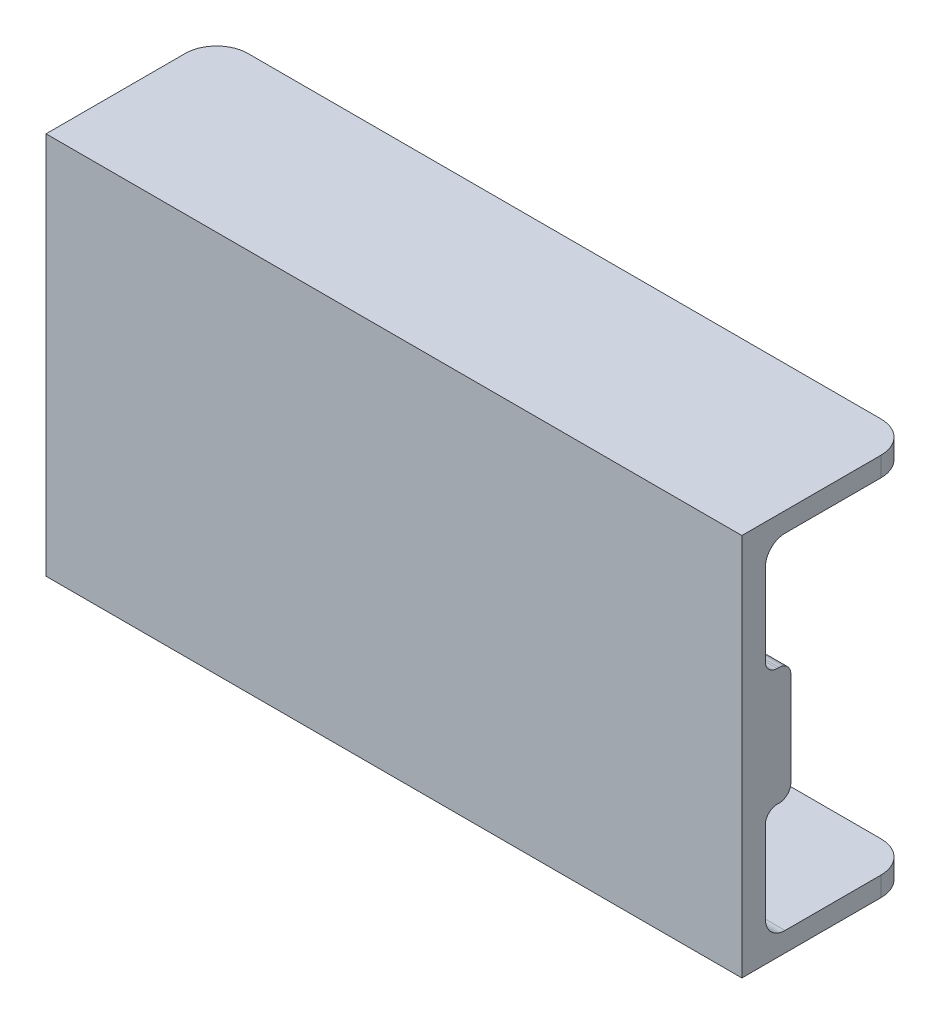
SolidWorks part; units mm, degrees
ref_plane "Front Plane" through (0, 0, 0) normal (0, 0, 1) x (1, 0, 0)
ref_plane "Top Plane" through (0, 0, 0) normal (0, 1, 0) x (1, 0, 0)
ref_plane "Right Plane" through (0, 0, 0) normal (1, 0, 0) x (0, 0, -1)
sketch "Sketch1" plane through (0, 0, 0) normal (0, 0, 1) x (1, 0, 0)
  line L1 (-17.75, -9.775) -> (17.75, -9.775)
  line L2 (-17.75, -9.775) -> (-17.75, 9.775)
  line L3 (-17.75, 9.775) -> (17.75, 9.775)
  line L4 (17.75, -9.775) -> (17.75, 9.775)
  line L5 (-17.75, -9.775) -> (17.75, 9.775) construction
  line L6 (-17.75, 9.775) -> (17.75, -9.775) construction
  point P0 (0, 0)
  dimension "D1" = 19.55
  dimension "D2" = 35.5
extrude "Boss-Extrude1" add sketch "Sketch1" along normal blind 1.2
sketch "Sketch2" plane through (0, 0, 0) normal (0, 0, -1) x (-1, 0, 0)
  line L0 (17.75, 9.775) -> (17.75, -9.775) construction
  line L1 (-17.75, 9.775) -> (17.75, 9.775)
  line L2 (-17.75, 9.775) -> (-17.75, 8.775)
  line L3 (-17.75, 8.775) -> (17.75, 8.775)
  line L4 (17.75, 9.775) -> (17.75, 8.775)
  line L6 (-17.75, -9.775) -> (17.75, -9.775)
  line L7 (-17.75, -9.775) -> (-17.75, -8.775)
  line L8 (-17.75, -8.775) -> (17.75, -8.775)
  line L9 (17.75, -9.775) -> (17.75, -8.775)
  dimension "D1" = 1
  dimension "D2" = 1
extrude "Boss-Extrude2" add sketch "Sketch2" along normal blind 7.5
fillet "Fillet1" radius 1 2 edges at (0, -8.775, 0) (0, 8.775, 0)
sketch "Sketch3" plane through (0, 0, 0) normal (0, 0, -1) x (-1, 0, 0)
  line L0 (17.75, 7.775) -> (17.75, -7.775) construction
  line L1 (17.75, 3) -> (16.75, 3)
  line L2 (17.75, 3) -> (17.75, -3)
  line L3 (17.75, -3) -> (16.75, -3)
  line L4 (16.75, 3) -> (16.75, -3)
  line L5 (0, 4.785) -> (0, -4.785) construction
  line L6 (-17.75, 3) -> (-17.75, -3)
  line L7 (-17.75, -3) -> (-16.75, -3)
  line L8 (-17.75, 3) -> (-16.75, 3)
  line L9 (-16.75, 3) -> (-16.75, -3)
  dimension "D1" = 1
  dimension "D2" = 6
  dimension "D3" = 3
extrude "Boss-Extrude3" add sketch "Sketch3" along normal blind 1.3
fillet "Fillet2" radius 0.6 8 edges at (17.25, 3, 0) (17.25, -3, 0) (-17.25, 3, 0) (-17.25, -3, 0) (17.25, 3, -1.3) (17.25, -3, -1.3) (-17.25, 3, -1.3) (-17.25, -3, -1.3)
fillet "Fillet3" radius 1.6 4 edges at (17.75, -9.275, -7.5) (17.75, 9.275, -7.5) (-17.75, 9.275, -7.5) (-17.75, -9.275, -7.5)
